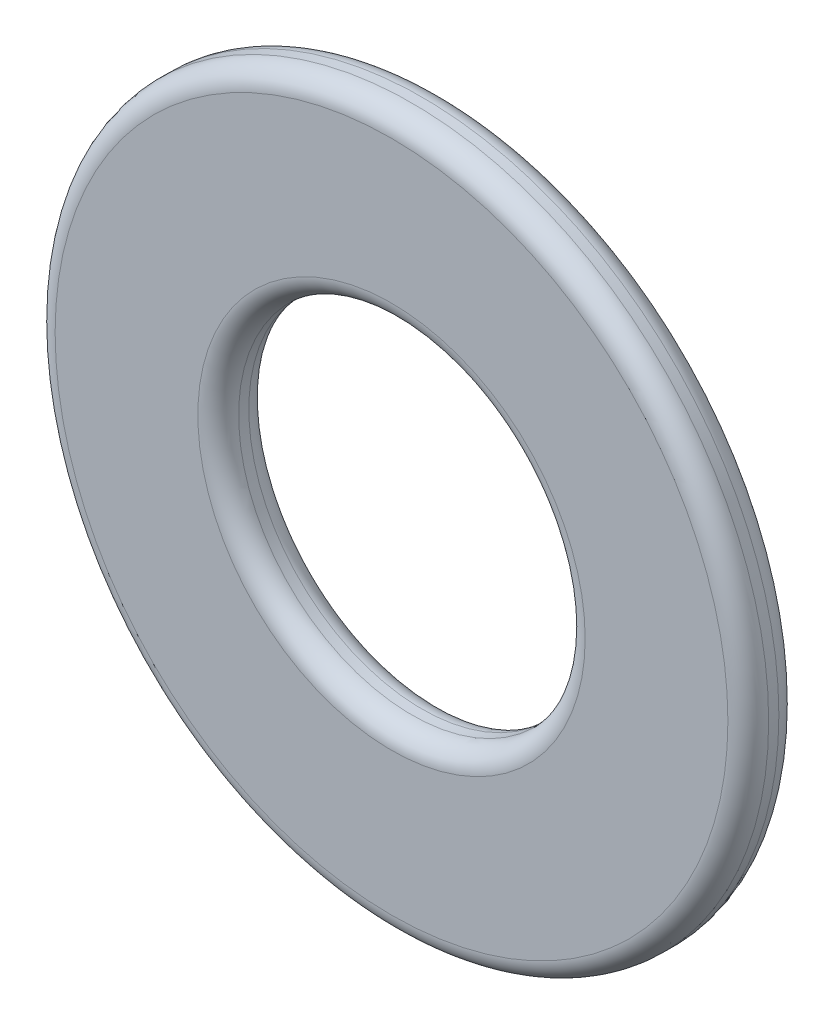
SolidWorks part; units mm, degrees
ref_plane "Plano frontal" through (0, 0, 0) normal (0, 0, 1) x (1, 0, 0)
ref_plane "Plano superior" through (0, 0, 0) normal (0, 1, 0) x (1, 0, 0)
ref_plane "Plano direito" through (0, 0, 0) normal (1, 0, 0) x (0, 0, -1)
sketch "Esboço1" plane through (0, 0, 0) normal (0, 0, 1) x (1, 0, 0)
  circle A0 centre (0, 0) radius 1.7
  circle A1 centre (0, 0) radius 3.5
  dimension "D1" = 3.4
  dimension "D2" = 7
extrude "Ressalto-extrusão1" add sketch "Esboço1" along normal blind 0.5
fillet "Filete1" radius 0.2 4 edges at (1.7, 0, 0) (3.5, 0, 0) (1.7, 0, 0.5) (3.5, 0, 0.5)
